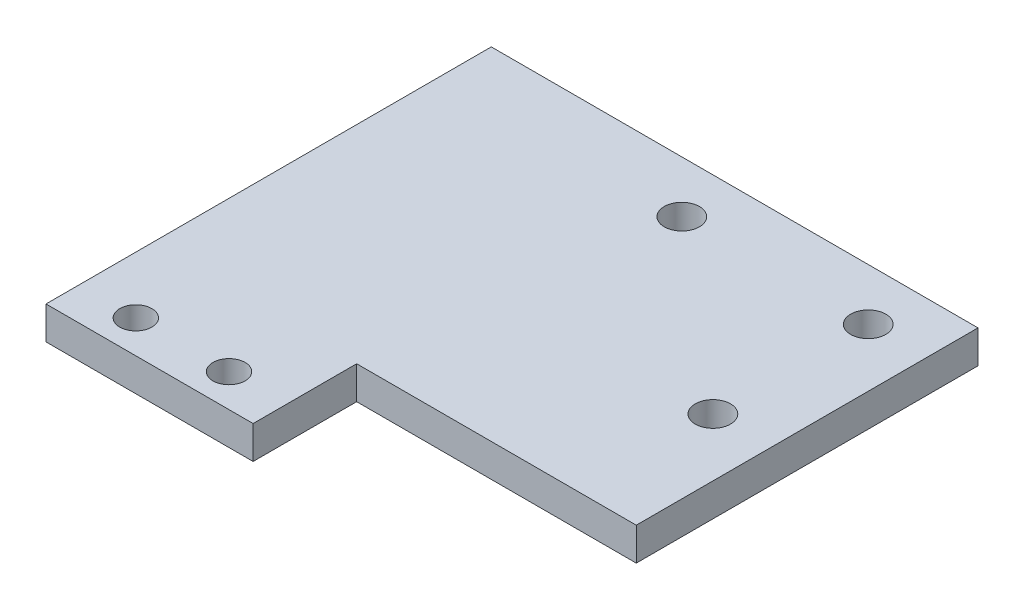
SolidWorks part; units mm, degrees
material "6061 Alloy"
ref_plane "Front Plane" through (0, 0, 0) normal (0, 0, 1) x (1, 0, 0)
ref_plane "Top Plane" through (0, 0, 0) normal (0, 1, 0) x (1, 0, 0)
ref_plane "Right Plane" through (0, 0, 0) normal (1, 0, 0) x (0, 0, -1)
sketch "Sketch1" plane through (0, 0, 0) normal (0, 1, 0) x (1, 0, 0)
  line L0 (0, 0) -> (0, 43)
  line L1 (0, 43) -> (47, 43)
  line L2 (47, 43) -> (47, 10)
  line L3 (47, 10) -> (20, 10)
  line L4 (20, 10) -> (20, 0)
  line L5 (0, 0) -> (20, 0)
  line L16 (20, 0) -> (20, 6.35) construction
  line L17 (14.5, 3.175) -> (5.5, 3.175) construction
  circle A6 centre (14.5, 3.175) radius 1.55
  circle A9 centre (5.5, 3.175) radius 1.55
  circle A12 centre (41.4, 23) radius 1.7 construction
  circle A13 centre (41.4, 38) radius 1.7 construction
  circle A14 centre (23.4, 38) radius 1.7 construction
  circle A15 centre (41.4, 23) radius 1.7
  circle A16 centre (41.4, 38) radius 1.7
  circle A17 centre (23.4, 38) radius 1.7
  point P20 (10, 3.175)
  point P21 (10, 0)
  dimension "D2" = 3.1
  dimension "D3" = 3.1
  dimension "D1" = 33
  dimension "D9" = 47
  dimension "D11" = 10
  dimension "D4" = 9
  dimension "D5" = 3.175
extrude "Boss-Extrude1" add sketch "Sketch1" along normal blind 3.175
equation "\"D3@Sketch1\"=\"D2@Sketch1\""
